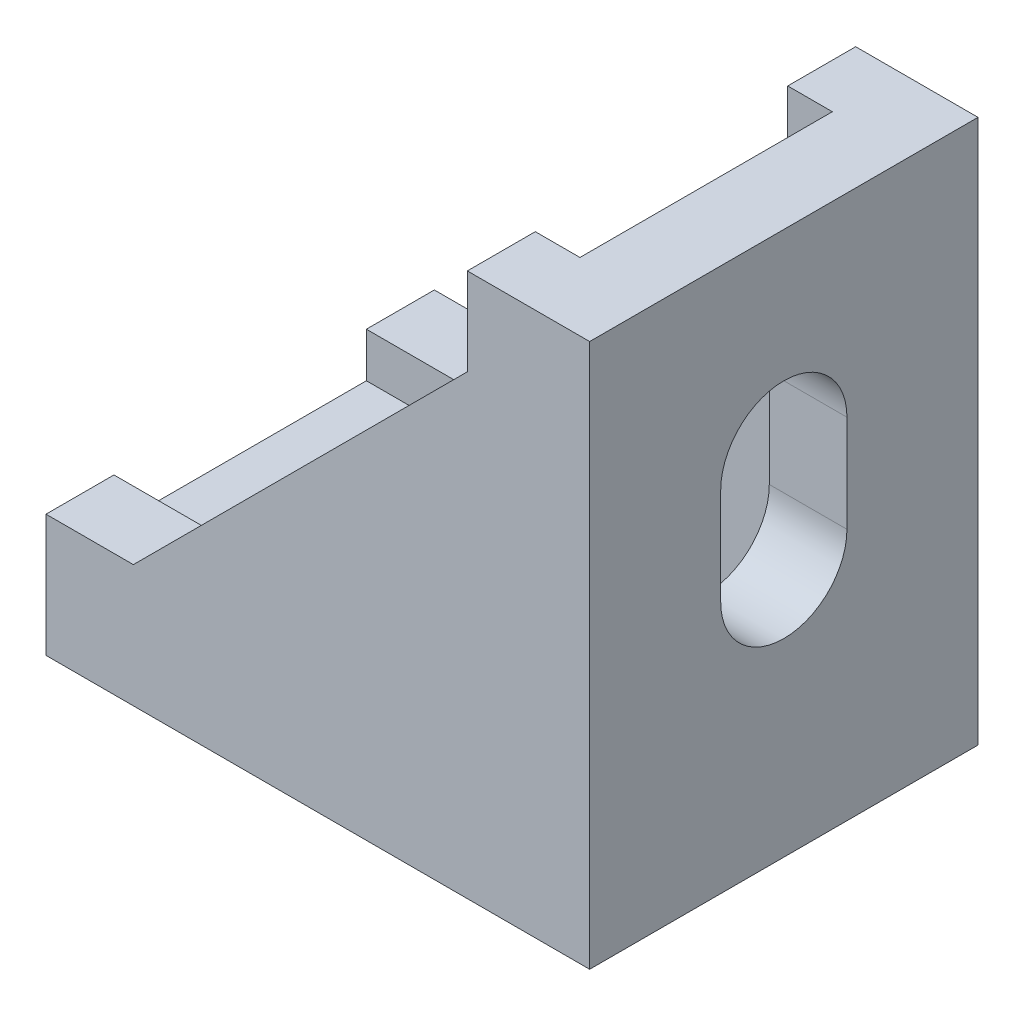
SolidWorks part; units mm, degrees
ref_plane "前视基准面" through (0, 0, 0) normal (0, 0, 1) x (1, 0, 0)
ref_plane "上视基准面" through (0, 0, 0) normal (0, 1, 0) x (1, 0, 0)
ref_plane "右视基准面" through (0, 0, 0) normal (1, 0, 0) x (0, 0, -1)
sketch "草图1" plane through (0, 0, 0) normal (0, 0, 1) x (1, 0, 0)
  line L1 (14, -14) -> (-14, -14)
  line L2 (14, -14) -> (14, 14)
  line L3 (14, 14) -> (10, 14)
  line L4 (-14, -14) -> (-14, -10)
  line L10 (10, 14) -> (10, -10)
  line L11 (10, -10) -> (-14, -10)
  point P0 (0, 0)
  dimension "D2" = 28
  dimension "D4" = 4
  dimension "D3" = 4
extrude "凸台-拉伸1" add sketch "草图1" along normal blind 20
sketch "草图3" plane through (0, 0, 0) normal (0, 0, -1) x (-1, 0, 0)
  line L0 (-10, 14) -> (-7.7, 14)
  line L1 (-7.7, 14) -> (-7.7, 9.5)
  line L2 (-7.7, 9.5) -> (9.5, -7.7)
  line L3 (9.5, -7.7) -> (14, -7.7)
  line L4 (14, -7.7) -> (14, -10)
  line L5 (-10, 14) -> (-14, 14)
  line L6 (-14, 14) -> (-14, -14)
  line L7 (-14, -14) -> (14, -14)
  line L8 (14, -14) -> (14, -10)
  point P10 (0, 0)
  point P11 (-10, 14)
  dimension "D1" = 6.3
  dimension "D2" = 6.3
  dimension "D3" = 4.5
  dimension "D4" = 4.5
extrude "凸台-拉伸2" add sketch "草图3" against normal blind 3.5
ref_plane "基准面5" through (0, 0, 10) normal (0, 0, 1) x (1, 0, 0)
mirror "镜向2" about plane through (0, 0, 10) normal (0, 0, 1) of "凸台-拉伸2"
sketch "草图6" plane through (10, 0, 0) normal (-1, 0, 0) x (0, 0, 1)
  line L0 (10, 4) -> (10, -1) construction
  line L1 (10, -15.4) -> (10, 15.4) construction
  line L2 (13.25, 4) -> (13.25, -1)
  line L3 (6.75, 4) -> (6.75, -1)
  line L4 (20, -14) -> (0, -14) construction
  arc A0 (13.25, 4) -> (6.75, 4) centre (10, 4) ccw
  arc A1 (6.75, -1) -> (13.25, -1) centre (10, -1) ccw
  point P4 (10, 1.5)
  dimension "D1" = 6.5
  dimension "D2" = 5
  dimension "D3" = 13
extrude "切除-拉伸2" cut sketch "草图6" against normal through all
sketch "草图8" plane through (0, -10, 0) normal (0, 1, 0) x (1, 0, 0)
  line L0 (-4, -10) -> (1, -10) construction
  line L1 (-15.4, -10) -> (15.4, -10) construction
  line L2 (-4, -6.75) -> (1, -6.75)
  line L3 (-4, -13.25) -> (1, -13.25)
  line L4 (14, -20) -> (14, 0) construction
  arc A0 (-4, -6.75) -> (-4, -13.25) centre (-4, -10) ccw
  arc A1 (1, -13.25) -> (1, -6.75) centre (1, -10) ccw
  point P4 (-1.5, -10)
  dimension "D1" = 6.5
  dimension "D2" = 5
  dimension "D3" = 13
extrude "切除-拉伸3" cut sketch "草图8" against normal through all
